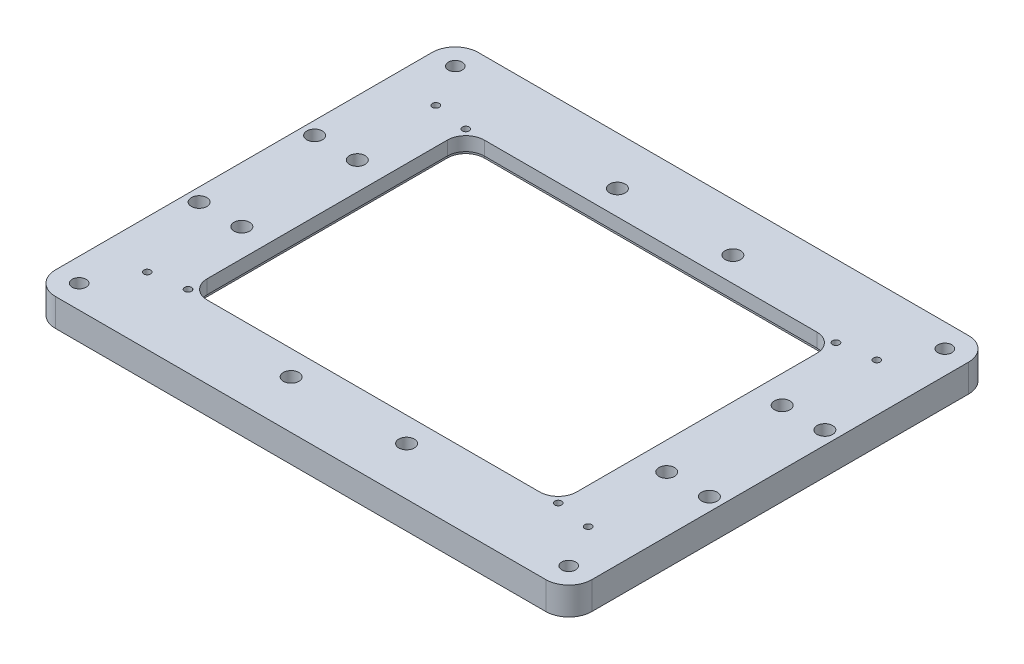
SolidWorks part; units mm, degrees
ref_plane "Спереди" through (0, 0, 0) normal (0, 0, 1) x (1, 0, 0)
ref_plane "Сверху" through (0, 0, 0) normal (0, 1, 0) x (1, 0, 0)
ref_plane "Справа" through (0, 0, 0) normal (1, 0, 0) x (0, 0, -1)
sketch "Эскиз2" plane through (0, 0, 0) normal (0, 1, 0) x (1, 0, 0)
  line L1 (-80, -60) -> (80, -60)
  line L2 (-80, -60) -> (-80, 60)
  line L3 (-80, 60) -> (80, 60)
  line L4 (80, -60) -> (80, 60)
  line L5 (-80, -60) -> (80, 60) construction
  line L6 (-80, 60) -> (80, -60) construction
  line L7 (-110, -75) -> (110, -75)
  line L8 (-110, -75) -> (-110, 75)
  line L9 (-110, 75) -> (110, 75)
  line L10 (110, -75) -> (110, 75)
  line L11 (-110, -75) -> (110, 75) construction
  line L12 (-110, 75) -> (110, -75) construction
  point P0 (0, 0)
  point P6 (0, 0)
  dimension "D1" = 120
  dimension "D2" = 160
extrude "Бобышка-Вытянуть1" add sketch "Эскиз2" along normal blind 12
sketch "Эскиз3" plane through (0, 0, 0) normal (0, -1, 0) x (1, 0, 0)
  line L1 (-85.25, -65.25) -> (85.25, -65.25)
  line L2 (-85.25, -65.25) -> (-85.25, 65.25)
  line L3 (-85.25, 65.25) -> (85.25, 65.25)
  line L4 (85.25, -65.25) -> (85.25, 65.25)
  line L5 (-85.25, -65.25) -> (85.25, 65.25) construction
  line L6 (-85.25, 65.25) -> (85.25, -65.25) construction
  point P0 (0, 0)
extrude "Вырез-Вытянуть1" cut sketch "Эскиз3" against normal blind 6
fillet "Скругление1" radius 8 1 edges at (80, 9, 60)
fillet "Скругление2" radius 8 1 edges at (85.25, 3, 65.25)
fillet "Скругление3" radius 8 6 edges at (80, 9, -60) (85.25, 3, -65.25) (-80, 9, 60) (-85.25, 3, 65.25) (-80, 9, -60) (-85.25, 3, -65.25)
sketch "Эскиз4" plane through (0, 6, 0) normal (0, -1, 0) x (1, 0, 0)
  circle A0 centre (-80.15, 60.15) radius 1.5
  circle A1 centre (-80.15, -60.15) radius 1.5
  circle A2 centre (80.15, -60.15) radius 1.5
  circle A3 centre (80.15, 60.15) radius 1.5
  circle A4 centre (-95.5, 62.5) radius 1.5
  circle A5 centre (-95.5, -62.5) radius 1.5
  circle A6 centre (95.5, -62.5) radius 1.5
  circle A7 centre (95.5, 62.5) radius 1.5
extrude "Вырез-Вытянуть2" cut sketch "Эскиз4" against normal through all both and the other way through all from surface at 6 starting at face at (0, 0, 0)
sketch "Эскиз6" plane through (0, 0, 0) normal (0, -1, 0) x (1, 0, 0)
  line L1 (120.7617, 91.7099) -> (-120.7617, 91.7099)
  line L2 (120.7617, 91.7099) -> (120.7617, -91.7099)
  line L3 (120.7617, -91.7099) -> (-120.7617, -91.7099)
  line L4 (-120.7617, 91.7099) -> (-120.7617, -91.7099)
  line L5 (120.7617, 91.7099) -> (-120.7617, -91.7099) construction
  line L6 (120.7617, -91.7099) -> (-120.7617, 91.7099) construction
  line L7 (-105.3372, -71.7154) -> (105.3372, -71.7154)
  line L8 (-105.3372, -71.7154) -> (-105.3372, 71.7154)
  line L9 (-105.3372, 71.7154) -> (105.3372, 71.7154)
  line L10 (105.3372, -71.7154) -> (105.3372, 71.7154)
  line L11 (-105.3372, -71.7154) -> (105.3372, 71.7154) construction
  line L12 (-105.3372, 71.7154) -> (105.3372, -71.7154) construction
  point P0 (0, 0)
  point P6 (0, 0)
extrude "Бобышка-Вытянуть2" add sketch "Эскиз6" against normal blind 12
sketch "Эскиз5" plane through (0, 0, 0) normal (0, -1, 0) x (1, 0, 0)
  line L0 (0, 0) -> (0, 116.455) construction
  line L1 (0, 0) -> (46.8208, 0) construction
  circle A2 centre (-92.0064, -25) radius 3.3655
  circle A3 centre (-110.4976, -25) radius 3.3655
  circle A8 centre (-110.4976, 25) radius 3.3655
  circle A9 centre (-92.0064, 25) radius 3.3655
  circle A10 centre (92.0064, 25) radius 3.3655
  circle A11 centre (110.4976, 25) radius 3.3655
  circle A12 centre (110.4976, -25) radius 3.3655
  circle A13 centre (92.0064, -25) radius 3.3655
  circle A26 centre (25, 70.6611) radius 3.3655
  circle A27 centre (-25, 70.6611) radius 3.3655
  circle A29 centre (-25, -70.6611) radius 3.3655
  circle A30 centre (25, -70.6611) radius 3.3655
extrude "Вырез-Вытянуть3" cut sketch "Эскиз5" against normal blind 22
sketch "Эскиз7" plane through (0, 0, 0) normal (0, -1, 0) x (1, 0, 0)
  line L0 (0, -81.4508) -> (-106.0202, -81.4508) construction
  line L1 (0, 0) -> (0, 40.3237) construction
  line L2 (0, 0) -> (39.7171, 0) construction
  circle A0 centre (-106.0202, -81.4508) radius 3
  circle A1 centre (-106.0202, 81.4508) radius 3
  circle A2 centre (106.0202, 81.4508) radius 3
  circle A3 centre (106.0202, -81.4508) radius 3
extrude "Вырез-Вытянуть4" cut sketch "Эскиз7" against normal blind 22
sketch "Эскиз8" plane through (-120.7617, 0, 0) normal (-1, 0, 0) x (0, 0, 1)
  line L0 (0, 0) -> (0, 12) construction
  line L1 (-80, 6) -> (-78.0056, 7.1514) construction
  line L6 (91.7099, 0) -> (-91.7099, 0) construction
  line L7 (91.7099, 12) -> (-91.7099, 12) construction
  line L8 (0, 6) -> (-80, 6) construction
  line L9 (-82.0145, 7.1631) -> (-80, 6) construction
  line L10 (-79.8871, 3.7393) -> (-77.9892, 7.0266)
  line L11 (-78.1055, 7.2281) -> (-81.9156, 7.2281)
  line L12 (-82.0343, 7.0672) -> (-80.1129, 3.7393)
  line L13 (-80, 6) -> (-80, 3.6925) construction
  line L14 (-91.7099, 6) -> (-92.8614, 7.9944) construction
  line L15 (-92.873, 3.9855) -> (-91.7099, 6) construction
  line L16 (-89.4492, 6.1129) -> (-92.7365, 8.0108)
  line L17 (-92.938, 7.8945) -> (-92.938, 4.0844)
  line L18 (-92.7771, 3.9657) -> (-89.4492, 5.8871)
  line L19 (-91.7099, 6) -> (-89.4024, 6) construction
  line L20 (-69.8871, 3.7393) -> (-67.9892, 7.0266)
  line L21 (-68.1055, 7.2281) -> (-71.9156, 7.2281)
  line L22 (-72.0343, 7.0672) -> (-70.1129, 3.7393)
  line L23 (-70, 6) -> (-68.0056, 7.1514) construction
  line L24 (-72.0145, 7.1631) -> (-70, 6) construction
  line L25 (-70, 6) -> (-70, 3.6925) construction
  line L26 (70, 6) -> (70, 3.6925) construction
  line L27 (72.0145, 7.1631) -> (70, 6) construction
  line L28 (70, 6) -> (68.0056, 7.1514) construction
  line L29 (91.7099, 6) -> (89.4024, 6) construction
  line L30 (92.873, 3.9855) -> (91.7099, 6) construction
  line L31 (91.7099, 6) -> (92.8614, 7.9944) construction
  line L32 (80, 6) -> (80, 3.6925) construction
  line L33 (82.0145, 7.1631) -> (80, 6) construction
  line L34 (80, 6) -> (78.0056, 7.1514) construction
  line L35 (72.0343, 7.0672) -> (70.1129, 3.7393)
  line L36 (68.1055, 7.2281) -> (71.9156, 7.2281)
  line L37 (69.8871, 3.7393) -> (67.9892, 7.0266)
  line L38 (92.7771, 3.9657) -> (89.4492, 5.8871)
  line L39 (92.938, 7.8945) -> (92.938, 4.0844)
  line L40 (89.4492, 6.1129) -> (92.7365, 8.0108)
  line L41 (82.0343, 7.0672) -> (80.1129, 3.7393)
  line L42 (78.1055, 7.2281) -> (81.9156, 7.2281)
  line L43 (79.8871, 3.7393) -> (77.9892, 7.0266)
  circle A0 centre (-80, 6) radius 1.2281 construction
  arc A1 (-82.0343, 7.0672) -> (-81.9156, 7.2281) centre (-81.8945, 7.0884) cw
  arc A2 (-78.1055, 7.2281) -> (-77.9892, 7.0266) centre (-78.1481, 7.0692) cw
  arc A3 (-80.1129, 3.7393) -> (-79.8871, 3.7393) centre (-80, 3.8522) ccw
  circle A4 centre (-91.7099, 6) radius 1.2281 construction
  arc A5 (-92.7771, 3.9657) -> (-92.938, 4.0844) centre (-92.7983, 4.1055) cw
  arc A6 (-92.938, 7.8945) -> (-92.7365, 8.0108) centre (-92.7791, 7.8519) cw
  arc A7 (-89.4492, 5.8871) -> (-89.4492, 6.1129) centre (-89.5621, 6) ccw
  arc A8 (-72.0343, 7.0672) -> (-71.9156, 7.2281) centre (-71.8945, 7.0884) cw
  arc A9 (-68.1055, 7.2281) -> (-67.9892, 7.0266) centre (-68.1481, 7.0692) cw
  arc A10 (-70.1129, 3.7393) -> (-69.8871, 3.7393) centre (-70, 3.8522) ccw
  circle A11 centre (-70, 6) radius 1.2281 construction
  circle A12 centre (70, 6) radius 1.2281 construction
  circle A13 centre (91.7099, 6) radius 1.2281 construction
  circle A14 centre (80, 6) radius 1.2281 construction
  arc A15 (70.1129, 3.7393) -> (69.8871, 3.7393) centre (70, 3.8522) cw
  arc A16 (68.1055, 7.2281) -> (67.9892, 7.0266) centre (68.1481, 7.0692) ccw
  arc A17 (72.0343, 7.0672) -> (71.9156, 7.2281) centre (71.8945, 7.0884) ccw
  arc A18 (89.4492, 5.8871) -> (89.4492, 6.1129) centre (89.5621, 6) cw
  arc A19 (92.938, 7.8945) -> (92.7365, 8.0108) centre (92.7791, 7.8519) ccw
  arc A20 (92.7771, 3.9657) -> (92.938, 4.0844) centre (92.7983, 4.1055) ccw
  arc A21 (80.1129, 3.7393) -> (79.8871, 3.7393) centre (80, 3.8522) cw
  arc A22 (78.1055, 7.2281) -> (77.9892, 7.0266) centre (78.1481, 7.0692) ccw
  arc A23 (82.0343, 7.0672) -> (81.9156, 7.2281) centre (81.8945, 7.0884) ccw
  dimension "D1" = 2
sketch "Эскиз9" plane through (0, 0, 91.7099) normal (0, 0, 1) x (1, 0, 0)
  line L0 (0, -3.9761) -> (0, 32.7247) construction
  line L1 (-109.0272, 5.9689) -> (-107.0329, 7.1204) construction
  line L2 (-111.0417, 7.132) -> (-109.0272, 5.9689) construction
  line L3 (-108.9144, 3.7082) -> (-107.0164, 6.9955)
  line L4 (-107.1328, 7.197) -> (-110.9429, 7.197)
  line L5 (-111.0615, 7.0362) -> (-109.1401, 3.7082)
  line L6 (-109.0272, 5.9689) -> (-109.0272, 3.6615) construction
  line L7 (-120.7372, 5.9689) -> (-121.8886, 7.9633) construction
  line L8 (-121.9002, 3.9544) -> (-120.7372, 5.9689) construction
  line L9 (-118.4764, 6.0818) -> (-121.7638, 7.9797)
  line L10 (-121.9653, 7.8634) -> (-121.9653, 4.0533)
  line L11 (-121.8044, 3.9347) -> (-118.4764, 5.8561)
  line L12 (-120.7372, 5.9689) -> (-118.4297, 5.9689) construction
  line L13 (-98.9144, 3.7082) -> (-97.0164, 6.9955)
  line L14 (-97.1328, 7.197) -> (-100.9429, 7.197)
  line L15 (-101.0615, 7.0362) -> (-99.1401, 3.7082)
  line L16 (-99.0272, 5.9689) -> (-97.0329, 7.1204) construction
  line L17 (-101.0417, 7.132) -> (-99.0272, 5.9689) construction
  line L18 (-99.0272, 5.9689) -> (-99.0272, 3.6615) construction
  line L19 (99.0272, 5.9689) -> (99.0272, 3.6615) construction
  line L20 (101.0417, 7.132) -> (99.0272, 5.9689) construction
  line L21 (99.0272, 5.9689) -> (97.0329, 7.1204) construction
  line L22 (120.7372, 5.9689) -> (118.4297, 5.9689) construction
  line L23 (121.9002, 3.9544) -> (120.7372, 5.9689) construction
  line L24 (120.7372, 5.9689) -> (121.8886, 7.9633) construction
  line L25 (109.0272, 5.9689) -> (109.0272, 3.6615) construction
  line L26 (111.0417, 7.132) -> (109.0272, 5.9689) construction
  line L27 (109.0272, 5.9689) -> (107.0329, 7.1204) construction
  line L28 (101.0615, 7.0362) -> (99.1401, 3.7082)
  line L29 (97.1328, 7.197) -> (100.9429, 7.197)
  line L30 (98.9144, 3.7082) -> (97.0164, 6.9955)
  line L31 (121.8044, 3.9347) -> (118.4764, 5.8561)
  line L32 (121.9653, 7.8634) -> (121.9653, 4.0533)
  line L33 (118.4764, 6.0818) -> (121.7638, 7.9797)
  line L34 (111.0615, 7.0362) -> (109.1401, 3.7082)
  line L35 (107.1328, 7.197) -> (110.9429, 7.197)
  line L36 (108.9144, 3.7082) -> (107.0164, 6.9955)
  circle A0 centre (-109.0272, 5.9689) radius 1.2281 construction
  arc A1 (-111.0615, 7.0362) -> (-110.9429, 7.197) centre (-110.9218, 7.0573) cw
  arc A2 (-107.1328, 7.197) -> (-107.0164, 6.9955) centre (-107.1754, 7.0381) cw
  arc A3 (-109.1401, 3.7082) -> (-108.9144, 3.7082) centre (-109.0272, 3.8211) ccw
  circle A4 centre (-120.7372, 5.9689) radius 1.2281 construction
  arc A5 (-121.8044, 3.9347) -> (-121.9653, 4.0533) centre (-121.8255, 4.0744) cw
  arc A6 (-121.9653, 7.8634) -> (-121.7638, 7.9797) centre (-121.8064, 7.8208) cw
  arc A7 (-118.4764, 5.8561) -> (-118.4764, 6.0818) centre (-118.5893, 5.9689) ccw
  arc A8 (-101.0615, 7.0362) -> (-100.9429, 7.197) centre (-100.9218, 7.0573) cw
  arc A9 (-97.1328, 7.197) -> (-97.0164, 6.9955) centre (-97.1754, 7.0381) cw
  arc A10 (-99.1401, 3.7082) -> (-98.9144, 3.7082) centre (-99.0272, 3.8211) ccw
  circle A11 centre (-99.0272, 5.9689) radius 1.2281 construction
  circle A12 centre (99.0272, 5.9689) radius 1.2281 construction
  circle A13 centre (120.7372, 5.9689) radius 1.2281 construction
  circle A14 centre (109.0272, 5.9689) radius 1.2281 construction
  arc A15 (99.1401, 3.7082) -> (98.9144, 3.7082) centre (99.0272, 3.8211) cw
  arc A16 (97.1328, 7.197) -> (97.0164, 6.9955) centre (97.1754, 7.0381) ccw
  arc A17 (101.0615, 7.0362) -> (100.9429, 7.197) centre (100.9218, 7.0573) ccw
  arc A18 (118.4764, 5.8561) -> (118.4764, 6.0818) centre (118.5893, 5.9689) cw
  arc A19 (121.9653, 7.8634) -> (121.7638, 7.9797) centre (121.8064, 7.8208) ccw
  arc A20 (121.8044, 3.9347) -> (121.9653, 4.0533) centre (121.8255, 4.0744) ccw
  arc A21 (109.1401, 3.7082) -> (108.9144, 3.7082) centre (109.0272, 3.8211) cw
  arc A22 (107.1328, 7.197) -> (107.0164, 6.9955) centre (107.1754, 7.0381) ccw
  arc A23 (111.0615, 7.0362) -> (110.9429, 7.197) centre (110.9218, 7.0573) ccw
fillet "Скругление4" radius 6 1 edges at (120.7617, 6, 91.7099)
fillet "Скругление5" radius 6 1 edges at (120.7617, 6, -91.7099)
fillet "Скругление6" radius 6 1 edges at (-120.7617, 6, -91.7099)
fillet "Скругление7" radius 6 1 edges at (-120.7617, 6, 91.7099)
sketch "Эскиз11" plane through (0, 12, 0) normal (0, 1, 0) x (1, 0, 0)
  line L0 (-106.0202, 81.4508) -> (-106.0202, -81.4508) construction
  line L1 (-106.0202, 0) -> (-82.6364, 0) construction
  line L2 (0, 42.7673) -> (0, -26.2865) construction
  line L3 (-109.5202, -65) -> (-102.5202, -65)
  line L4 (-109.5202, -65) -> (-109.5202, 65)
  line L5 (-109.5202, 65) -> (-102.5202, 65)
  line L6 (-102.5202, -65) -> (-102.5202, 65)
  line L7 (-109.5202, -65) -> (-102.5202, 65) construction
  line L8 (-109.5202, 65) -> (-102.5202, -65) construction
  line L9 (109.5202, 65) -> (102.5202, -65) construction
  line L10 (109.5202, -65) -> (102.5202, 65) construction
  line L11 (102.5202, -65) -> (102.5202, 65)
  line L12 (109.5202, 65) -> (102.5202, 65)
  line L13 (109.5202, -65) -> (109.5202, 65)
  line L14 (109.5202, -65) -> (102.5202, -65)
  line L15 (-106.0202, 81.4508) -> (106.0202, 81.4508) construction
  line L16 (0, 0) -> (41.0984, 0) construction
  line L17 (-90, 77.9352) -> (90, 77.9352)
  line L18 (-90, 77.9352) -> (-90, 84.9665)
  line L19 (-90, 84.9665) -> (90, 84.9665)
  line L20 (90, 77.9352) -> (90, 84.9665)
  line L21 (-90, 77.9352) -> (90, 84.9665) construction
  line L22 (-90, 84.9665) -> (90, 77.9352) construction
  line L23 (-90, -84.9665) -> (90, -77.9352) construction
  line L24 (-90, -77.9352) -> (90, -84.9665) construction
  line L25 (90, -77.9352) -> (90, -84.9665)
  line L26 (-90, -84.9665) -> (90, -84.9665)
  line L27 (-90, -77.9352) -> (-90, -84.9665)
  line L28 (-90, -77.9352) -> (90, -77.9352)
  point P18 (0, 81.4508)
  point P31 (0, -81.4508)
sketch "Эскиз14" plane through (0, 12, 0) normal (0, 1, 0) x (1, 0, 0)
  line L1 (-88.5855, 112.9617) -> (91.4145, 112.9617)
  line L2 (-88.5855, 112.9617) -> (-88.5855, 105.9304)
  line L3 (-88.5855, 105.9304) -> (91.4145, 105.9304)
  line L4 (91.4145, 112.9617) -> (91.4145, 105.9304)
  line L5 (-71.4512, 122.0821) -> (-71.4512, 115.0821)
  line L6 (-71.4512, 122.0821) -> (58.5488, 122.0821)
  line L7 (58.5488, 122.0821) -> (58.5488, 115.0821)
  line L8 (-71.4512, 115.0821) -> (58.5488, 115.0821)
  line L16 (-88.4614, 132.6226) -> (91.5386, 132.6226)
  line L17 (-88.4614, 132.6226) -> (-88.4614, 125.5913)
  line L18 (-88.4614, 125.5913) -> (91.5386, 125.5913)
  line L19 (91.5386, 132.6226) -> (91.5386, 125.5913)
  line L20 (-71.3271, 141.7431) -> (-71.3271, 134.7431)
  line L21 (-71.3271, 141.7431) -> (58.6729, 141.7431)
  line L22 (58.6729, 141.7431) -> (58.6729, 134.7431)
  line L23 (-71.3271, 134.7431) -> (58.6729, 134.7431)
  circle A0 centre (-81.5856, 109.4133) radius 2
  circle A1 centre (1.4145, 109.4133) radius 2
  circle A2 centre (84.4145, 109.4133) radius 2
  circle A3 centre (51.5488, 118.5821) radius 2
  circle A4 centre (-6.4512, 118.5821) radius 2
  circle A5 centre (-64.4512, 118.5821) radius 2
  circle A12 centre (-81.4615, 129.0742) radius 2
  circle A13 centre (1.5386, 129.0742) radius 2
  circle A14 centre (84.5387, 129.0742) radius 2
  circle A15 centre (51.6729, 138.2431) radius 2
  circle A16 centre (-6.3271, 138.2431) radius 2
  circle A17 centre (-64.3271, 138.2431) radius 2
extrude "Бобышка-Вытянуть3" add sketch "Эскиз14" against normal up to surface (12 mm away) separate body up to face at (106.0202, 0, -78.4508)
sketch "Эскиз15" plane through (0, 0, 0) normal (0, -1, 0) x (1, 0, 0)
  line L1 (-116.1648, 91.5435) -> (116.1648, 91.5435)
  line L2 (-116.1648, 91.5435) -> (-116.1648, -91.5435)
  line L3 (-116.1648, -91.5435) -> (116.1648, -91.5435)
  line L4 (116.1648, 91.5435) -> (116.1648, -91.5435)
  line L5 (-116.1648, 91.5435) -> (116.1648, -91.5435) construction
  line L6 (-116.1648, -91.5435) -> (116.1648, 91.5435) construction
  line L7 (-230.3583, 201.8215) -> (230.3583, 201.8215)
  line L8 (-230.3583, 201.8215) -> (-230.3583, -201.8215)
  line L9 (-230.3583, -201.8215) -> (230.3583, -201.8215)
  line L10 (230.3583, 201.8215) -> (230.3583, -201.8215)
  line L11 (-230.3583, 201.8215) -> (230.3583, -201.8215) construction
  line L12 (-230.3583, -201.8215) -> (230.3583, 201.8215) construction
  arc A0 (114.7617, -91.7099) -> (120.7617, -85.7099) centre (114.7617, -85.7099) ccw construction
  point P0 (0, 0)
  point P9 (0, 0)
extrude "Вырез-Вытянуть8" cut sketch "Эскиз15" against normal blind 105
fillet "Скругление8" radius 10 4 edges at (116.1648, 6, -91.5435) (116.1648, 6, 91.5435) (-116.1648, 6, 91.5435) (-116.1648, 6, -91.5435)
